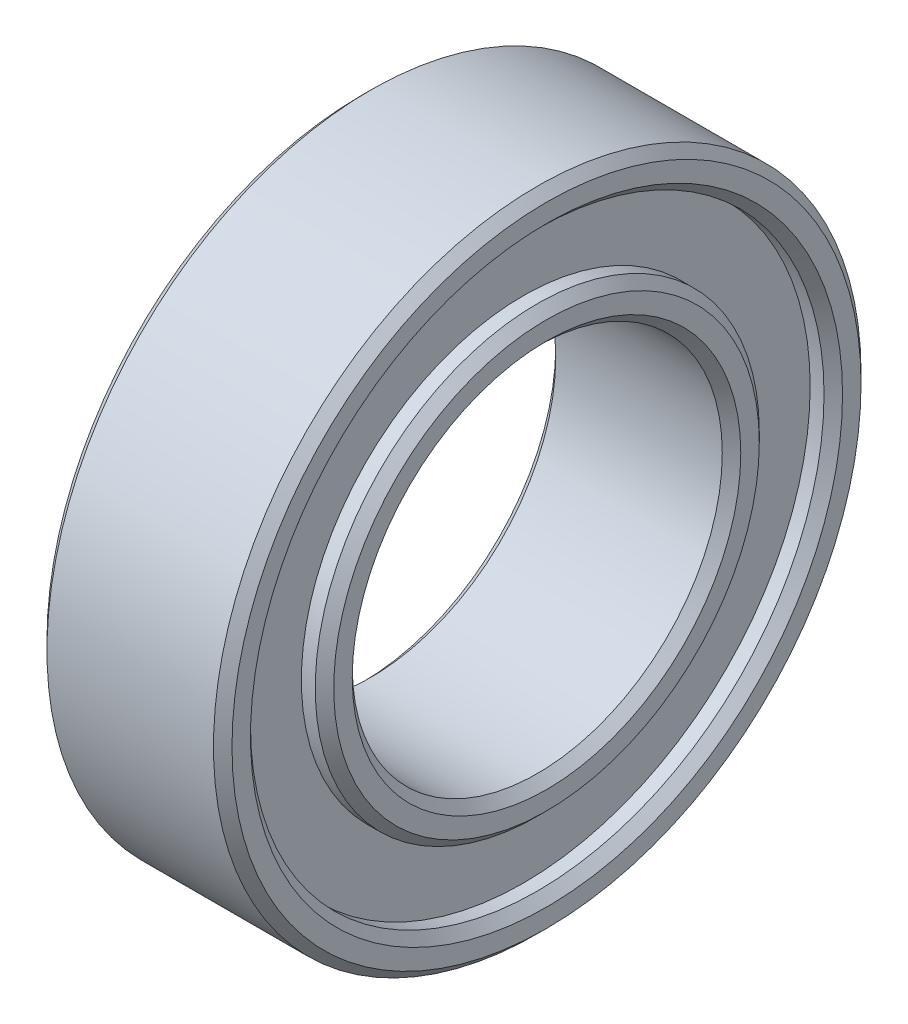
SolidWorks part; units mm, degrees
ref_plane "Front Plane" through (0, 0, 0) normal (0, 0, 1) x (1, 0, 0)
ref_plane "Top Plane" through (0, 0, 0) normal (0, 1, 0) x (1, 0, 0)
ref_plane "Right Plane" through (0, 0, 0) normal (1, 0, 0) x (0, 0, -1)
sketch "Sketch1" plane through (0, 0, 0) normal (1, 0, 0) x (0, 0, -1)
  circle A0 centre (0, 0) radius 7
  circle A1 centre (0, 0) radius 4
  dimension "D1" = 8
  dimension "D2" = 14
extrude "Boss-Extrude1" add sketch "Sketch1" along normal mid plane 4
sketch "Sketch2" plane through (2, 0, 0) normal (1, 0, 0) x (0, 0, -1)
  line L0 (0, 6.2) -> (0, 7) construction
  line L1 (0, 4.8) -> (0, 4) construction
  circle A0 centre (0, 0) radius 6.2
  circle A1 centre (0, 0) radius 4.8
  circle A2 centre (0, 0) radius 7 construction
  circle A3 centre (0, 0) radius 4 construction
  dimension "D1" = 0.8
extrude "Cut-Extrude1" cut sketch "Sketch2" against normal blind 0.5
mirror "Mirror1" about plane through (0, 0, 0) normal (1, 0, 0) of "Cut-Extrude1"
chamfer "Chamfer1" distance 0.2 angle 45 8 edges at (-2, 0, -4.8) (-2, 0, -4) (-2, 0, -7) (-2, 0, -6.2) (2, 0, -4.8) (2, 0, -4) (2, 0, -7) (2, 0, -6.2)
